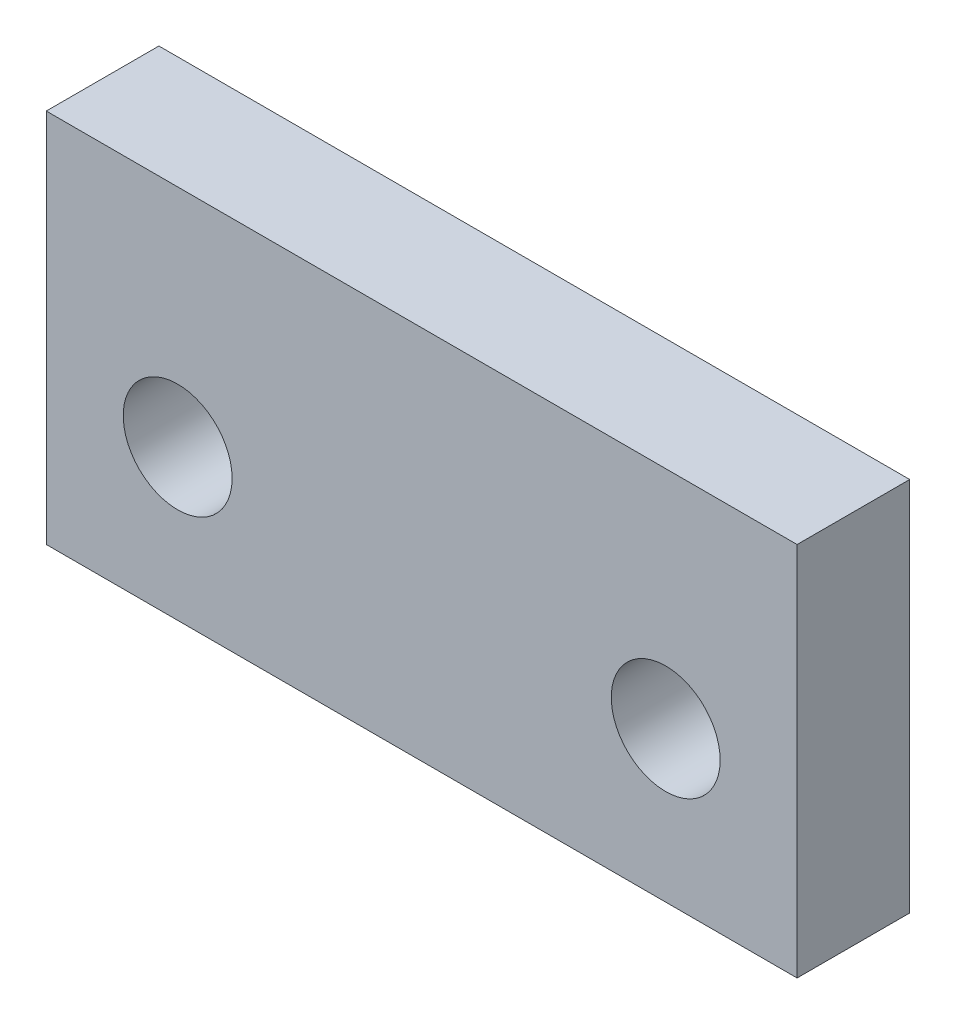
SolidWorks part; units mm, degrees
ref_plane "前视基准面" through (0, 0, 0) normal (0, 0, 1) x (1, 0, 0)
ref_plane "上视基准面" through (0, 0, 0) normal (0, 1, 0) x (1, 0, 0)
ref_plane "右视基准面" through (0, 0, 0) normal (1, 0, 0) x (0, 0, -1)
other "Configuration Table"
sketch "草图1" plane through (0, 0, 0) normal (0, 0, 1) x (1, 0, 0)
  line L1 (0, 0) -> (20, 0)
  line L2 (0, 0) -> (0, -10)
  line L3 (0, -10) -> (20, -10)
  line L4 (20, 0) -> (20, -10)
  circle A0 centre (3.5, -6) radius 1.45
  circle A1 centre (16.5, -6) radius 1.45
  dimension "D3" = 2.9
  dimension "D4" = 2.9
  dimension "D6" = 3.5
  dimension "D8" = 6
  dimension "D1" = 20
  dimension "D2" = 10
  dimension "D5" = 13
  dimension "D7" = 6
extrude "凸台-拉伸1" add sketch "草图1" along normal blind 3
